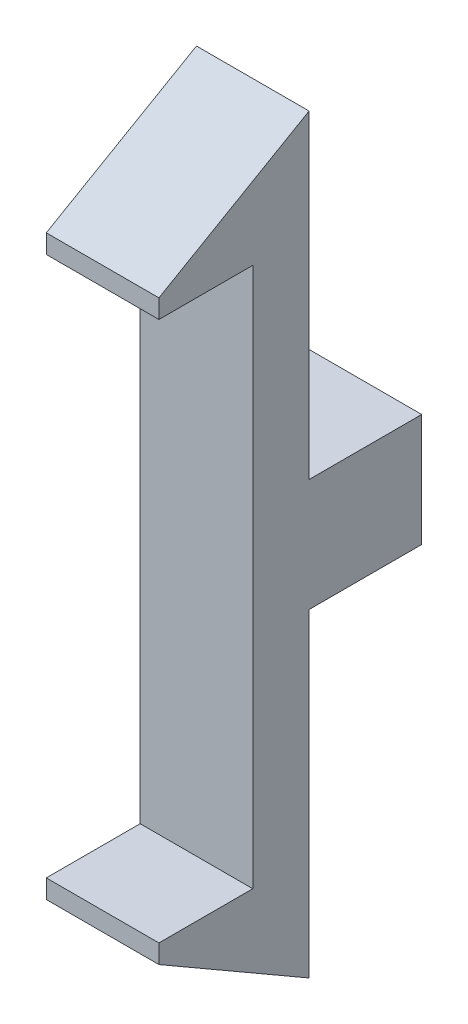
SolidWorks part; units mm, degrees
ref_plane "Front Plane" through (0, 0, 0) normal (0, 0, 1) x (1, 0, 0)
ref_plane "Top Plane" through (0, 0, 0) normal (0, 1, 0) x (1, 0, 0)
ref_plane "Right Plane" through (0, 0, 0) normal (1, 0, 0) x (0, 0, -1)
sketch "Sketch1" plane through (0, 0, 0) normal (0, 0, 1) x (1, 0, 0)
  line L1 (15, -15) -> (-15, -15)
  line L2 (15, -15) -> (15, 15)
  line L3 (15, 15) -> (-15, 15)
  line L4 (-15, -15) -> (-15, 15)
  line L5 (15, -15) -> (-15, 15) construction
  line L6 (15, 15) -> (-15, -15) construction
  point P0 (0, 0)
  dimension "D1" = 30
extrude "Boss-Extrude1" add sketch "Sketch1" along normal blind 30
sketch "Sketch2" plane through (0, 0, 0) normal (1, 0, 0) x (0, 0, -1)
  line L0 (-30, 15) -> (-30, 100)
  line L1 (-70, 71.906) -> (-70, 76.906)
  line L2 (-70, 71.906) -> (-45, 71.906)
  line L3 (-45, 71.906) -> (-45, 0)
  line L4 (-45, 0) -> (-30, 0)
  line L5 (-30, -15) -> (-30, 15) construction
  line L6 (-70, 76.906) -> (-30, 100)
  line L7 (-30, 15) -> (-30, 0)
  dimension "D1" = 60
  dimension "D2" = 100
  dimension "D3" = 25
  dimension "D4" = 5
  dimension "D5" = 15
extrude "Boss-Extrude2" add sketch "Sketch2" along normal mid plane 30
mirror "Mirror1" about plane through (0, 0, 0) normal (0, 1, 0) of "Boss-Extrude2"
